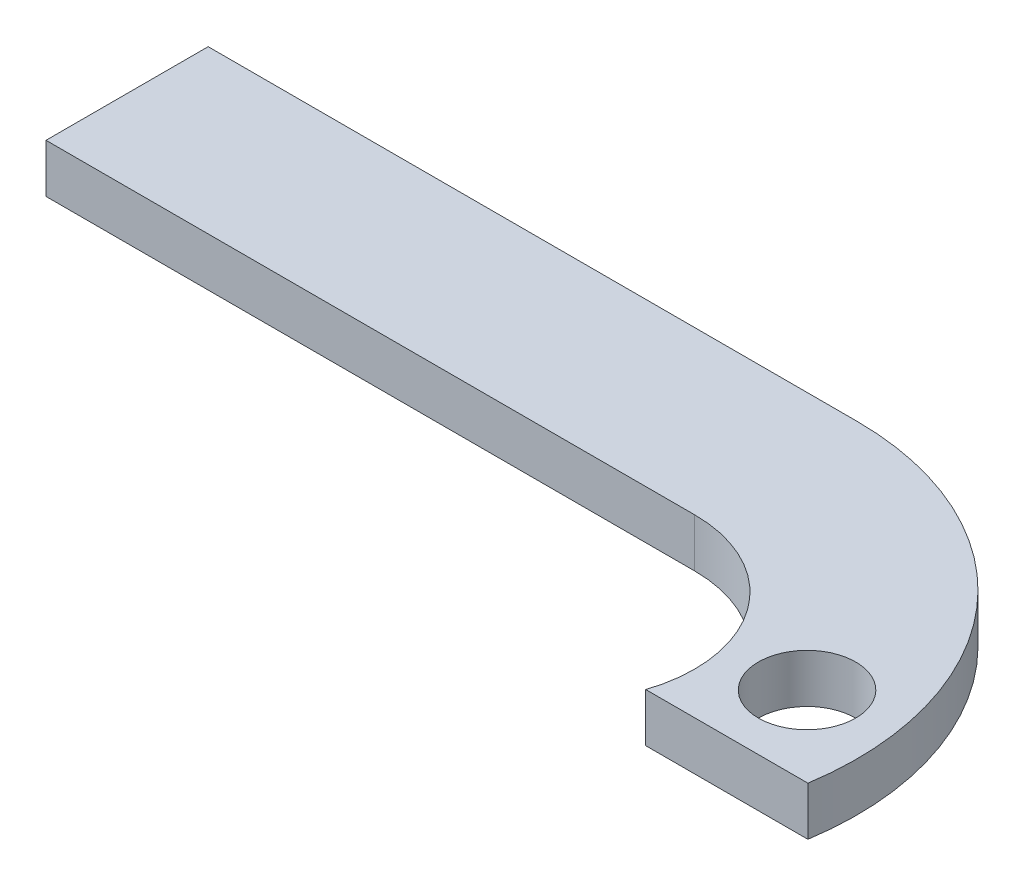
SolidWorks part; units mm, degrees
ref_plane "Front Plane" through (0, 0, 0) normal (0, 0, 1) x (1, 0, 0)
ref_plane "Top Plane" through (0, 0, 0) normal (0, 1, 0) x (1, 0, 0)
ref_plane "Right Plane" through (0, 0, 0) normal (1, 0, 0) x (0, 0, -1)
sketch "Sketch4" plane through (0, 0, 0) normal (0, 1, 0) x (1, 0, 0)
  line L0 (0, 0) -> (200, 0)
  line L1 (200, 0) -> (0, 0)
  line L2 (0, 0) -> (0, -50)
  line L3 (0, -50) -> (200, -50)
  line L4 (289.1243, -104.2035) -> (239.1243, -104.2035)
  line L5 (239.1243, -104.2035) -> (289.1243, -104.2035)
  line L6 (289.1243, -104.2035) -> (239.1243, -104.2035)
  arc A0 (200, 0) -> (289.1243, -104.2035) centre (200, -90.2154) cw
  arc A1 (289.1243, -104.2035) -> (200, 0) centre (200, -90.2154) ccw
  arc A2 (200, -50) -> (239.1243, -104.2035) centre (200, -91.2218) cw
extrude "Boss-Extrude1" add sketch "Sketch4" along normal blind 15 contours L3 A2 L4 A0 L0 L2
sketch "Sketch5" plane through (0, 15, 0) normal (0, 1, 0) x (1, 0, 0)
  circle A0 centre (264.1243, -79.4667) radius 15
extrude "Cut-Extrude1" cut sketch "Sketch5" against normal blind 31
